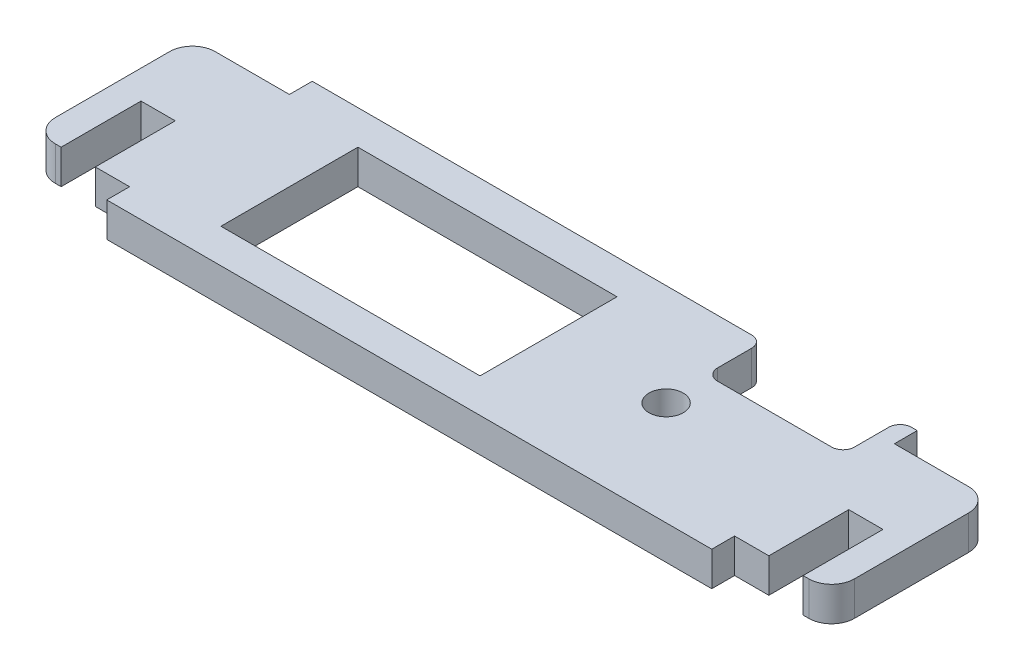
SolidWorks part; units mm, degrees
ref_plane "Front Plane" through (0, 0, 0) normal (0, 0, 1) x (1, 0, 0)
ref_plane "Top Plane" through (0, 0, 0) normal (0, 1, 0) x (1, 0, 0)
ref_plane "Right Plane" through (0, 0, 0) normal (1, 0, 0) x (0, 0, -1)
sketch "Sketch1" plane through (0, 0, 0) normal (0, 1, 0) x (1, 0, 0)
  line L5 (-9.8206, 11.01) -> (-9.8206, 1.01)
  line L7 (-79.8206, 1.01) -> (-79.8206, 11.01)
  line L15 (-77.8206, 13.01) -> (-71.3206, 13.01)
  line L17 (-77.8206, -0.99) -> (-71.3206, -0.99)
  line L21 (-71.3206, -0.99) -> (-71.3206, -2.99)
  line L22 (-71.3206, 13.01) -> (-71.3206, 15.01)
  line L24 (-71.3206, 15.01) -> (-32.8206, 15.01)
  line L26 (-18.3206, 13.01) -> (-11.8206, 13.01)
  line L27 (-11.8206, -0.99) -> (-18.3206, -0.99)
  line L28 (-18.3206, -0.99) -> (-18.3206, -2.99)
  line L29 (-18.3206, -2.99) -> (-71.3206, -2.99)
  line L30 (-18.3206, 13.01) -> (-18.3206, 15.01)
  line L31 (-18.3206, 15.01) -> (-18.8206, 15.01)
  line L32 (-19.8206, 14.01) -> (-19.8206, 11.01)
  line L33 (-20.8206, 10.01) -> (-30.8206, 10.01)
  line L34 (-31.8206, 11.01) -> (-31.8206, 14.01)
  arc A0 (-79.8206, 11.01) -> (-77.8206, 13.01) centre (-77.8206, 11.01) cw
  arc A1 (-11.8206, 13.01) -> (-9.8206, 11.01) centre (-11.8206, 11.01) cw
  arc A2 (-9.8206, 1.01) -> (-11.8206, -0.99) centre (-11.8206, 1.01) cw
  arc A3 (-77.8206, -0.99) -> (-79.8206, 1.01) centre (-77.8206, 1.01) cw
  arc A5 (-18.8206, 15.01) -> (-19.8206, 14.01) centre (-18.8206, 14.01) ccw
  arc A7 (-19.8206, 11.01) -> (-20.8206, 10.01) centre (-20.8206, 11.01) cw
  arc A8 (-30.8206, 10.01) -> (-31.8206, 11.01) centre (-30.8206, 11.01) cw
  arc A9 (-31.8206, 14.01) -> (-32.8206, 15.01) centre (-32.8206, 14.01) ccw
  dimension "D1" = 2
  dimension "D2" = 2
  dimension "D3" = 2
  dimension "D4" = 2
  dimension "D6" = 14
  dimension "D8" = 8.5
  dimension "D9" = 2
  dimension "D11" = 1
  dimension "D12" = 1
  dimension "D14" = 1
  dimension "D10" = 1
  dimension "D5" = 70
  dimension "D13" = 5
  dimension "D15" = 12
  dimension "D16" = 53
  dimension "D17" = 0.5
extrude "Boss-Extrude1" add sketch "Sketch1" along normal blind 3
sketch "Sketch2" plane through (0, 3, 0) normal (0, 1, 0) x (1, 0, 0)
  line L1 (-64.3206, 12.01) -> (-41.6206, 12.01)
  line L2 (-64.3206, 12.01) -> (-64.3206, 0.01)
  line L3 (-64.3206, 0.01) -> (-41.6206, 0.01)
  line L4 (-41.6206, 12.01) -> (-41.6206, 0.01)
  line L7 (-32.8206, 15.01) -> (-71.3206, 15.01) construction
  line L8 (-71.3206, -0.99) -> (-71.3206, -2.99) construction
  dimension "D1" = 12
  dimension "D2" = 22.7
  dimension "D3" = 3
  dimension "D4" = 7
extrude "Cut-Extrude1" cut sketch "Sketch2" against normal blind 3
sketch "Sketch3" plane through (0, 3, 0) normal (0, 1, 0) x (1, 0, 0)
  line L0 (-18.3206, -0.99) -> (-11.8206, -0.99) construction
  line L1 (-15.3206, -0.99) -> (-12.3206, -0.99)
  line L2 (-15.3206, -0.99) -> (-15.3206, 6.01)
  line L3 (-15.3206, 6.01) -> (-12.3206, 6.01)
  line L4 (-12.3206, -0.99) -> (-12.3206, 6.01)
  line L5 (-18.3206, -2.99) -> (-18.3206, -0.99) construction
  line L6 (-11.8206, 13.01) -> (-18.3206, 13.01) construction
  line L7 (-77.8206, -0.99) -> (-71.3206, -0.99) construction
  line L8 (-74.3206, -0.99) -> (-77.3206, -0.99)
  line L9 (-74.3206, -0.99) -> (-74.3206, 6.01)
  line L10 (-74.3206, 6.01) -> (-77.3206, 6.01)
  line L11 (-77.3206, -0.99) -> (-77.3206, 6.01)
  line L12 (-71.3206, -0.99) -> (-71.3206, -2.99) construction
  dimension "D1" = 3
  dimension "D2" = 3
  dimension "D3" = 7
  dimension "D4" = 3
  dimension "D5" = 3
extrude "Cut-Extrude2" cut sketch "Sketch3" against normal blind 3
sketch "Sketch4" plane through (0, 3, 0) normal (0, 1, 0) x (1, 0, 0)
  line L1 (-9.8206, 1.01) -> (-9.8206, 11.01) construction
  line L2 (-32.8206, 15.01) -> (-71.3206, 15.01) construction
  circle A0 centre (-31.4206, 6.11) radius 1.5
  dimension "D1" = 3
  dimension "D2" = 8.9
  dimension "D3" = 21.6
extrude "Cut-Extrude3" cut sketch "Sketch4" against normal blind 3
